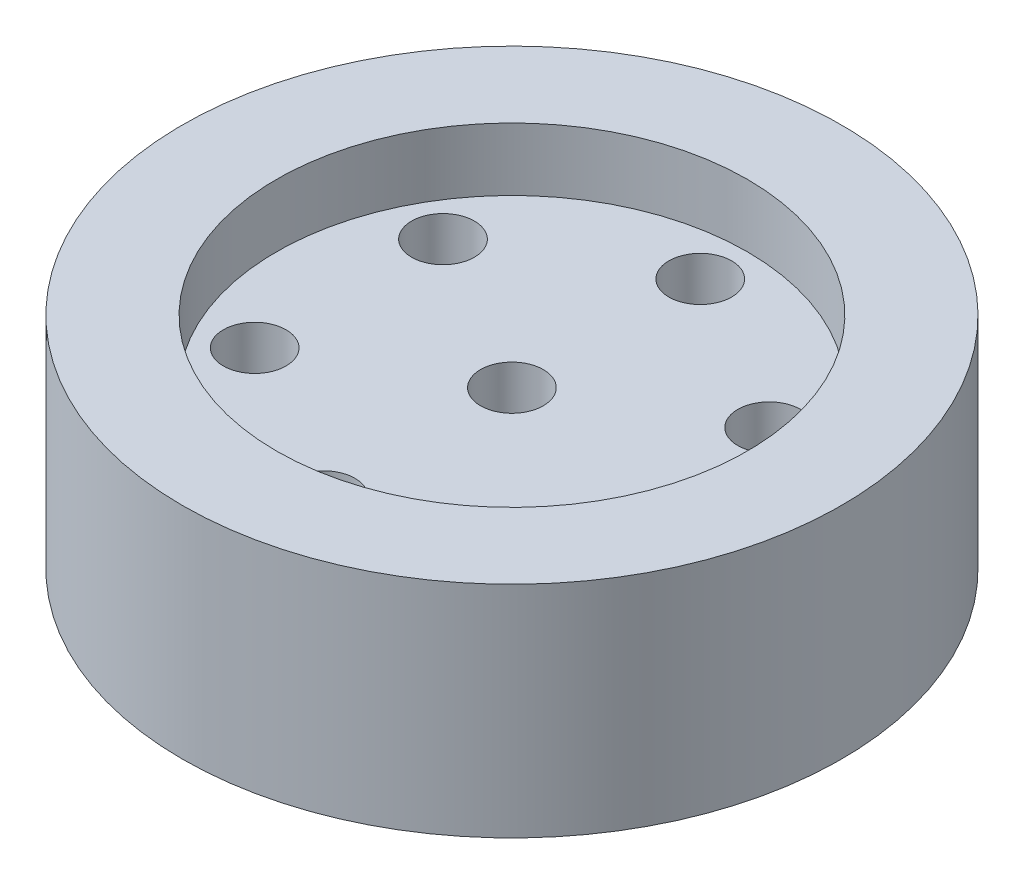
SolidWorks part; units mm, degrees
ref_plane "Front Plane" through (0, 0, 0) normal (0, 0, 1) x (1, 0, 0)
ref_plane "Top Plane" through (0, 0, 0) normal (0, 1, 0) x (1, 0, 0)
ref_plane "Right Plane" through (0, 0, 0) normal (1, 0, 0) x (0, 0, -1)
sketch "Sketch1" plane through (0, 0, 0) normal (0, 1, 0) x (1, 0, 0)
  circle A0 centre (0, 0) radius 21
extrude "Boss-Extrude1" add sketch "Sketch1" along normal blind 14
sketch "Sketch2" plane through (0, 14, 0) normal (0, 1, 0) x (1, 0, 0)
  circle A0 centre (0, 0) radius 15
extrude "Cut-Extrude1" cut sketch "Sketch2" against normal blind 4
sketch "Sketch3" plane through (0, 0, 0) normal (0, -1, 0) x (1, 0, 0)
  circle A0 centre (0, 0) radius 19
  circle A1 centre (0, 0) radius 5
  dimension "D1" = 38
  dimension "D2" = 10
extrude "Cut-Extrude2" cut sketch "Sketch3" against normal blind 4
sketch "Sketch4" plane through (0, 0, 0) normal (0, -1, 0) x (-1, 0, 0)
  circle A0 centre (0, 0) radius 2
extrude "Cut-Extrude3" cut sketch "Sketch4" against normal through all
sketch "Sketch5" plane through (0, 4, 0) normal (0, -1, 0) x (-1, 0, 0)
  circle A0 centre (0, 0) radius 12 construction
  circle A1 centre (0, -12) radius 2
  circle A2 centre (-10.3923, -6) radius 2
  circle A3 centre (-10.3923, 6) radius 2
  circle A4 centre (0, 12) radius 2
  circle A5 centre (10.3923, 6) radius 2
  circle A6 centre (10.3923, -6) radius 2
  point P17 (0, 0)
  dimension "D1" = 6
extrude "Cut-Extrude4" cut sketch "Sketch5" against normal through all
